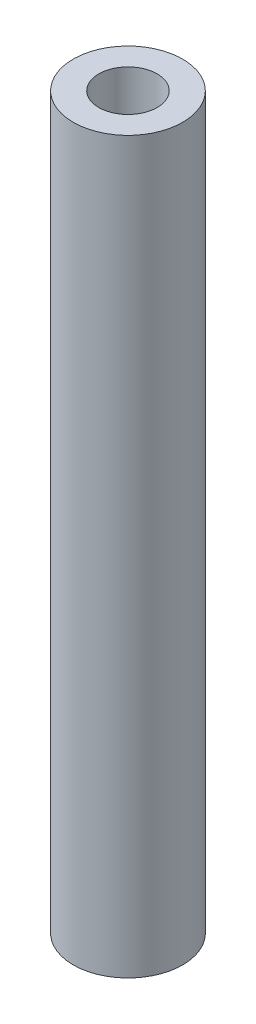
SolidWorks part; units mm, degrees
material "6061 Alloy"
ref_plane "Front Plane" through (0, 0, 0) normal (0, 0, 1) x (1, 0, 0)
ref_plane "Top Plane" through (0, 0, 0) normal (0, 1, 0) x (1, 0, 0)
ref_plane "Right Plane" through (0, 0, 0) normal (1, 0, 0) x (0, 0, -1)
sketch "SK_1" plane through (0, 0, 0) normal (0, 1, 0) x (1, 0, 0)
  circle A0 centre (0, 0) radius 3
  circle A1 centre (0, 0) radius 1.6
  dimension "Dia1" = 6
  dimension "Dia2" = 3.2
extrude "Spacer" add sketch "SK_1" along normal blind 40
equation "\"SO_L\" = 40 'spacer length"
equation "\"SO_D\" = 6 'outer diameter"
equation "\"SO_Bore\" = 3.2 'M3 bore"
equation "\"Dia1@SK_1\" = \"SO_D\""
equation "\"Dia2@SK_1\" = \"SO_Bore\""
equation "\"D1@Spacer\" = (\"SO_L\")-(0)"
